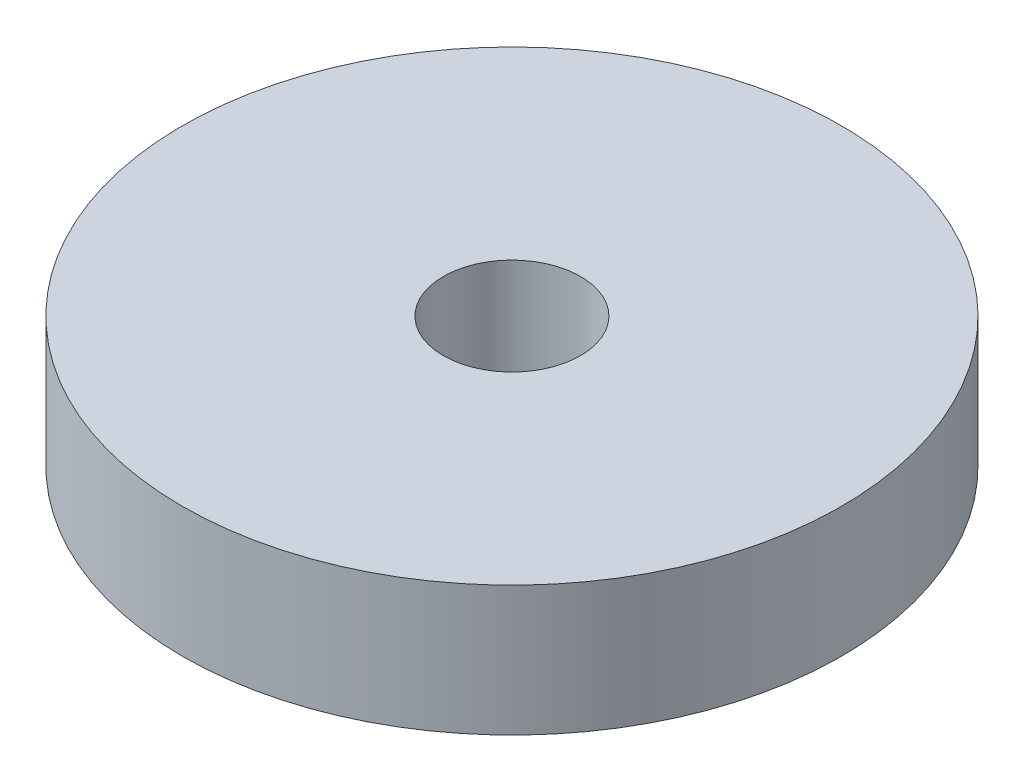
SolidWorks part; units mm, degrees
material "AISI 1020 Steel, Cold Rolled"
ref_plane "Front Plane" through (0, 0, 0) normal (0, 0, 1) x (1, 0, 0)
ref_plane "Top Plane" through (0, 0, 0) normal (0, 1, 0) x (1, 0, 0)
ref_plane "Right Plane" through (0, 0, 0) normal (1, 0, 0) x (0, 0, -1)
sketch "Sketch1" plane through (0, 0, 0) normal (0, 1, 0) x (1, 0, 0)
  circle A0 centre (0, 0) radius 1.585
  circle A1 centre (0, 0) radius 7.6136
  circle A2 centre (0, 0) radius 7.6136 construction
  dimension "D1" = 3.17
extrude "Boss-Extrude1" add sketch "Sketch1" along normal blind 3
